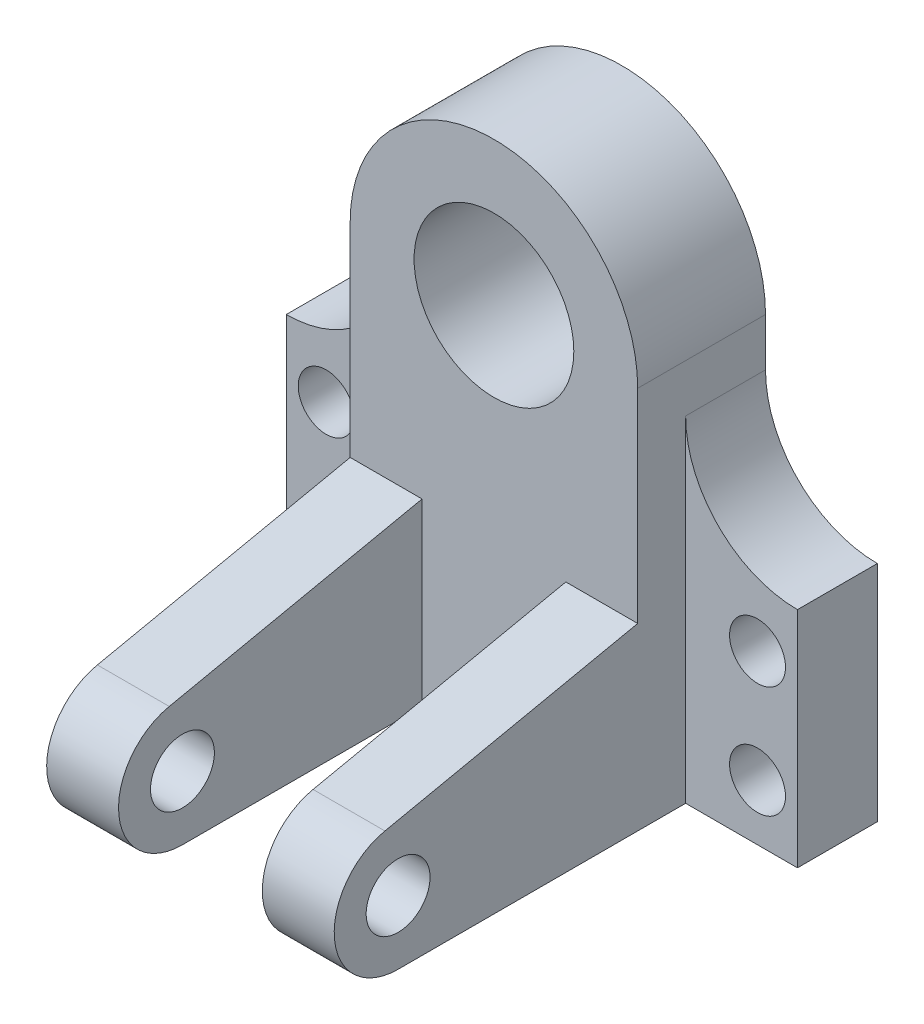
SolidWorks part; units mm, degrees
ref_plane "Front Plane" through (0, 0, 0) normal (0, 0, 1) x (1, 0, 0)
ref_plane "Top Plane" through (0, 0, 0) normal (0, 1, 0) x (1, 0, 0)
ref_plane "Right Plane" through (0, 0, 0) normal (1, 0, 0) x (0, 0, -1)
sketch "Sketch1" plane through (0, 0, 0) normal (0, 0, 1) x (1, 0, 0)
  line L4 (-36, 96) -> (-36, 0)
  line L5 (-36, 0) -> (36, 0)
  line L6 (36, 0) -> (36, 96)
  line L7 (0, 0) -> (0, 26.6062) construction
  arc A3 (36, 96) -> (-36, 96) centre (0, 96) ccw
  circle A4 centre (0, 96) radius 20
  dimension "D1" = 72
  dimension "D2" = 96
  dimension "D3" = 40
extrude "Boss-Extrude1" add sketch "Sketch1" along normal blind 32
sketch "Sketch2" plane through (0, 0, 0) normal (0, 0, 1) x (1, 0, 0)
  line L0 (36, 0) -> (64, 0)
  line L1 (64, 0) -> (64, 56)
  line L2 (36, 0) -> (36, 96) construction
  line L3 (36, 84) -> (36, 0)
  arc A0 (64, 56) -> (36, 84) centre (64, 84) cw
  dimension "D2" = 28
  dimension "D1" = 56
extrude "Boss-Extrude2" add sketch "Sketch2" along normal blind 20
mirror "Mirror1" about plane through (0, 0, 0) normal (1, 0, 0) of "Boss-Extrude2"
sketch "Sketch4" plane through (-36, 0, 0) normal (-1, 0, 0) x (0, 0, 1)
  line L0 (32, 0) -> (92, 0)
  line L1 (0, 0) -> (0, 56) construction
  line L2 (95.3004, 31.6559) -> (32, 45)
  line L3 (32, 96) -> (32, 0) construction
  line L4 (32, 45) -> (32, 0)
  line L5 (32, 132) -> (0, 132) construction
  arc A0 (92, 0) -> (95.3004, 31.6559) centre (92, 16) ccw
  circle A1 centre (92, 16) radius 8
  dimension "D2" = 32
  dimension "D4" = 16
  dimension "D1" = 92
  dimension "D3" = 87
extrude "Boss-Extrude3" add sketch "Sketch4" against normal blind 18
mirror "Mirror2" about plane through (0, 0, 0) normal (1, 0, 0) of "Boss-Extrude3"
hole_wizard "Hole1" positions "Sketch5" profile "Sketch6" legacy
sketch "Sketch5" plane through (0, 0, 20) normal (0, 0, 1) x (1, 0, 0)
  line L0 (36, 0) -> (64, 0) construction
  point P0 (54, 14)
  point P2 (54, 42)
  point P11 (51.8898, 13.7722)
  point P12 (0, 0)
  point P14 (0, 0)
  dimension "D1" = 28
  dimension "D2" = 14
  dimension "D3" = 54
sketch "Sketch6" plane through (54, 14, 20) normal (1, 0, 0) x (0, -1, 0)
  line L0 (0, 0) -> (0, 100)
  line L1 (0, 100) -> (7, 100)
  line L2 (7, 100) -> (7, 0)
  line L3 (7, 0) -> (0, 0)
  line L4 (0, 110) -> (0, -10) construction
  dimension "Diameter" = 14
  dimension "Depth" = 100
mirror "Mirror3" about plane through (0, 0, 0) normal (1, 0, 0) of "Hole1"
